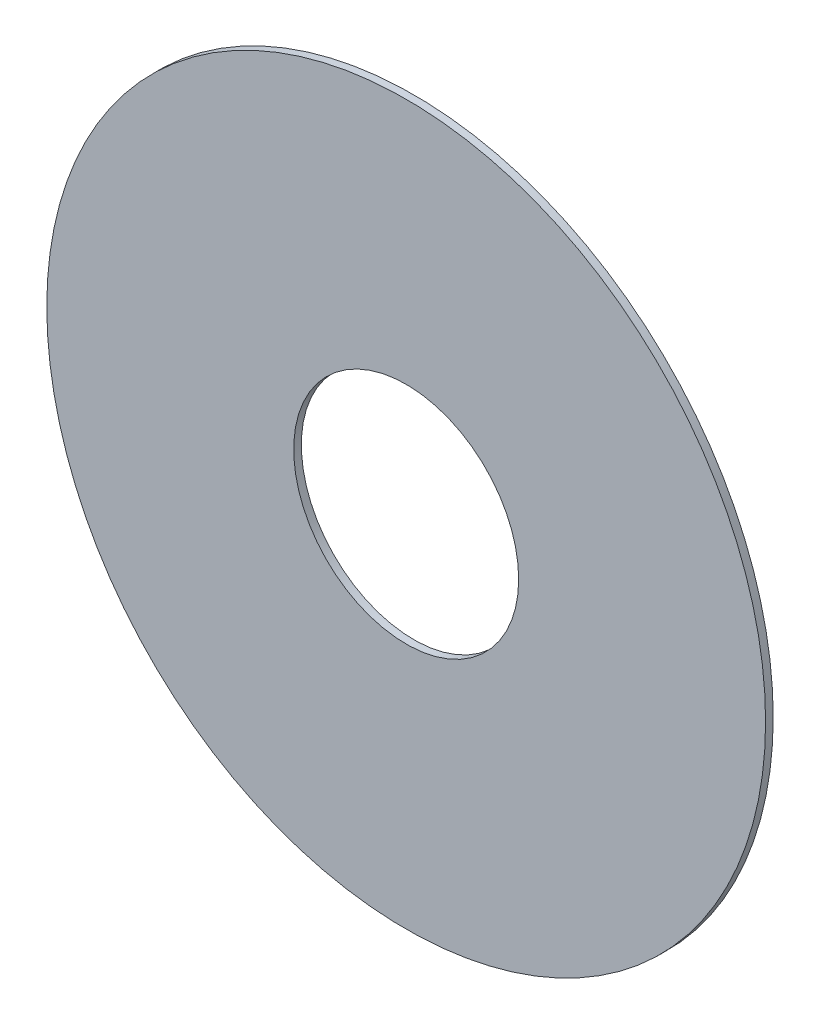
SolidWorks part; units mm, degrees
ref_plane "Спереди" through (0, 0, 0) normal (0, 0, 1) x (1, 0, 0)
ref_plane "Сверху" through (0, 0, 0) normal (0, 1, 0) x (1, 0, 0)
ref_plane "Справа" through (0, 0, 0) normal (1, 0, 0) x (0, 0, -1)
sketch "Эскиз1" plane through (0, 0, 0) normal (0, 0, 1) x (1, 0, 0)
  circle A0 centre (0, 0) radius 94.2462
  circle A1 centre (0, 0) radius 29.5
extrude "Printed_guard" add sketch "Эскиз1" along normal blind 2 from offset 47.5
